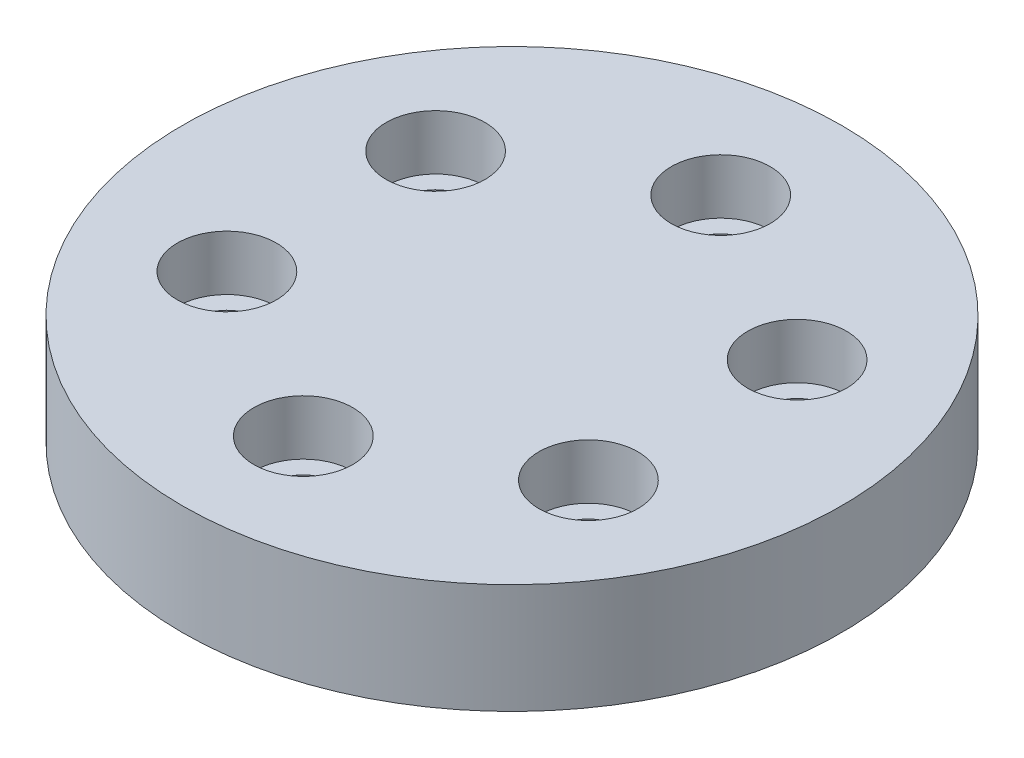
SolidWorks part; units mm, degrees
ref_plane "Front Plane" through (0, 0, 0) normal (0, 0, 1) x (1, 0, 0)
ref_plane "Top Plane" through (0, 0, 0) normal (0, 1, 0) x (1, 0, 0)
ref_plane "Right Plane" through (0, 0, 0) normal (1, 0, 0) x (0, 0, -1)
sketch "Sketch1" plane through (0, 0, 0) normal (0, 1, 0) x (1, 0, 0)
  circle A0 centre (0, 0) radius 30
  dimension "D1" = 60
extrude "Boss-Extrude1" add sketch "Sketch1" along normal blind 10
sketch "Sketch2" plane through (0, 10, 0) normal (0, 1, 0) x (1, 0, 0)
  circle A0 centre (0, 0) radius 19 construction
  circle A1 centre (0, 19) radius 4.5
  circle A2 centre (16.4545, 9.5) radius 4.5
  circle A3 centre (16.4545, -9.5) radius 4.5
  circle A4 centre (0, -19) radius 4.5
  circle A5 centre (-16.4545, -9.5) radius 4.5
  circle A6 centre (-16.4545, 9.5) radius 4.5
  point P5 (19.399, 10.3128)
  point P6 (0, 0)
  point P18 (0, 0)
  dimension "D1" = 38
  dimension "D2" = 9
  dimension "D3" = 6
extrude "Cut-Extrude1" cut sketch "Sketch2" against normal blind 5
sketch "Sketch3" plane through (0, 5, 0) normal (0, 1, 0) x (1, 0, 0)
  circle A0 centre (0, 19) radius 2.75
  circle A1 centre (16.4545, 9.5) radius 2.75
  circle A2 centre (16.4545, -9.5) radius 2.75
  circle A3 centre (0, -19) radius 2.75
  circle A4 centre (-16.4545, -9.5) radius 2.75
  circle A5 centre (-16.4545, 9.5) radius 2.75
  point P4 (0, 0)
  point P15 (0, 0)
  dimension "D1" = 5.5
  dimension "D2" = 6
extrude "Cut-Extrude2" cut sketch "Sketch3" against normal through all
sketch "Sketch8" plane through (0, 0, 0) normal (0, 0, 1) x (1, 0, 0)
  circle A0 centre (0, 50) radius 12.5
  circle A1 centre (0, 50) radius 22.5
  point P3 (-0.5368, 37.8873)
  point P4 (0, 50.4988)
  point P6 (15.2013, 36.9989)
  point P7 (0, 0)
  dimension "D1" = 25
  dimension "D2" = 10
